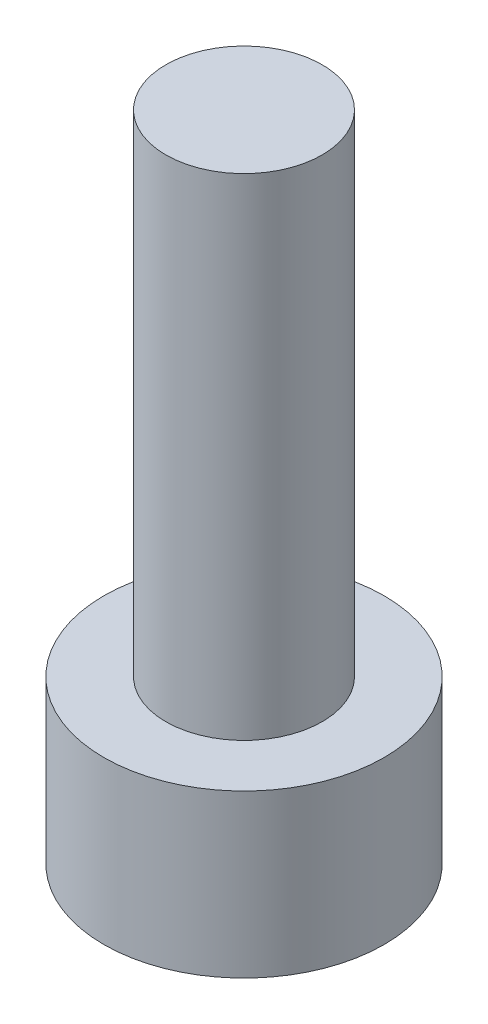
SolidWorks part; units mm, degrees
ref_plane "Front Plane" through (0, 0, 0) normal (0, 0, 1) x (1, 0, 0)
ref_plane "Top Plane" through (0, 0, 0) normal (0, 1, 0) x (1, 0, 0)
ref_plane "Right Plane" through (0, 0, 0) normal (1, 0, 0) x (0, 0, -1)
sketch "Sketch1" plane through (0, 0, 0) normal (0, 1, 0) x (1, 0, 0)
  circle A0 centre (0, 0) radius 1.73
  dimension "D1" = 3.46
extrude "Boss-Extrude1" add sketch "Sketch1" along normal blind 2
sketch "Sketch2" plane through (0, 2, 0) normal (0, 1, 0) x (1, 0, 0)
  circle A0 centre (0, 0) radius 0.965
  dimension "D1" = 1.93
extrude "Boss-Extrude2" add sketch "Sketch2" along normal blind 6.06
